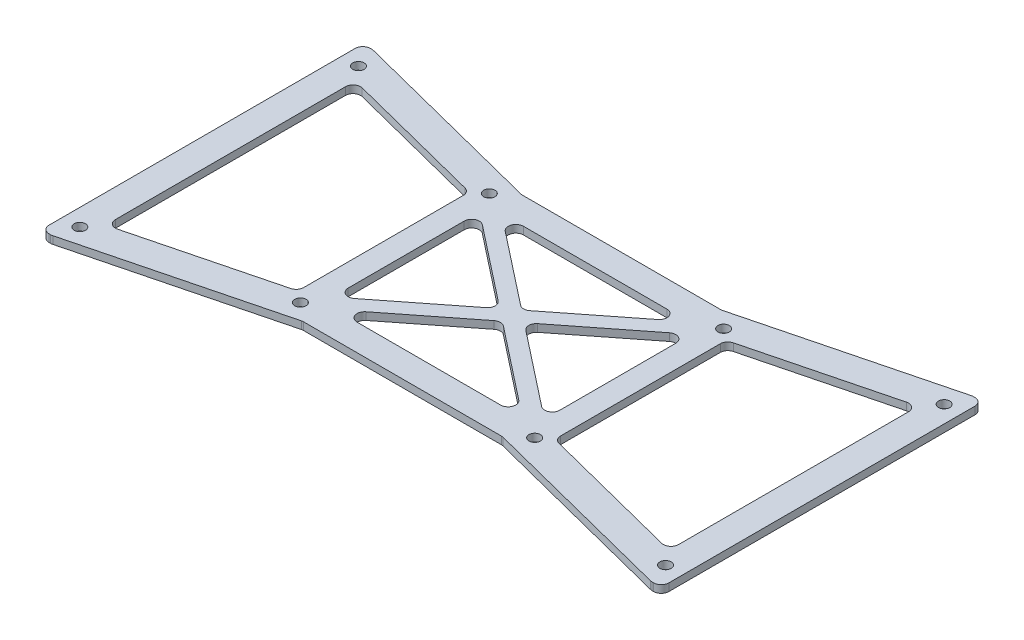
SolidWorks part; units mm, degrees
material "Thornel Mat VMA"
ref_plane "前视基准面" through (0, 0, 0) normal (0, 0, 1) x (1, 0, 0)
ref_plane "上视基准面" through (0, 0, 0) normal (0, 1, 0) x (1, 0, 0)
ref_plane "右视基准面" through (0, 0, 0) normal (1, 0, 0) x (0, 0, -1)
sketch "草图1" plane through (0, 0, 0) normal (0, 1, 0) x (1, 0, 0)
  line L1 (-82, -42.5) -> (82, -42.5)
  line L2 (-82, -42.5) -> (-82, 42.5)
  line L3 (-82, 42.5) -> (82, 42.5)
  line L4 (82, -42.5) -> (82, 42.5)
  line L5 (0, 42.5) -> (0, -42.5) construction
  line L6 (-82, 0) -> (82, 0) construction
  point P0 (0, 0)
  dimension "D1" = 164
  dimension "D2" = 85
extrude "凸台-拉伸1" add sketch "草图1" along normal blind 2
sketch "草图2" plane through (0, 2, 0) normal (0, 1, 0) x (1, 0, 0)
  line L1 (-31, -25) -> (31, -25) construction
  line L2 (-31, -25) -> (-31, 25) construction
  line L3 (-31, 25) -> (31, 25) construction
  line L4 (31, -25) -> (31, 25) construction
  line L5 (0, 25) -> (0, -25) construction
  line L6 (-31, 0) -> (31, 0) construction
  circle A0 centre (31, 25) radius 1.5
  circle A1 centre (-31, 25) radius 1.5
  circle A2 centre (-31, -25) radius 1.5
  circle A3 centre (31, -25) radius 1.5
  point P0 (0, 0)
  dimension "D3" = 3
  dimension "D1" = 62
  dimension "D2" = 50
extrude "切除-拉伸1" cut sketch "草图2" against normal blind 2
sketch "草图4" plane through (0, 2, 0) normal (0, 1, 0) x (1, 0, 0)
  line L1 (-28, -22) -> (28, -22)
  line L2 (-28, -22) -> (-28, 22)
  line L3 (-28, 22) -> (28, 22)
  line L4 (28, -22) -> (28, 22)
  line L5 (0, 22) -> (0, -22) construction
  line L6 (-28, 0) -> (28, 0) construction
  circle A0 centre (-31, 25) radius 1.5 construction
  point P0 (0, 0)
  dimension "D1" = 3
  dimension "D2" = 3
extrude "切除-拉伸3" cut sketch "草图4" against normal blind 10
sketch "草图7" plane through (0, 2, 0) normal (0, 1, 0) x (1, 0, 0)
  line L0 (-28, 22) -> (28, -22) construction
  line L1 (-28, -22) -> (28, 22) construction
  line L2 (-29.2356, 20.4274) -> (26.7644, -23.5726)
  line L3 (-26.7644, -23.5726) -> (29.2356, 20.4274)
  line L4 (-26.7644, 23.5726) -> (29.2356, -20.4274)
  line L5 (-29.2356, -20.4274) -> (26.7644, 23.5726)
  arc A0 (-29.2356, 20.4274) -> (-26.7644, 23.5726) centre (-28, 22) cw
  arc A1 (26.7644, -23.5726) -> (29.2356, -20.4274) centre (28, -22) ccw
  arc A2 (-26.7644, -23.5726) -> (-29.2356, -20.4274) centre (-28, -22) cw
  arc A3 (29.2356, 20.4274) -> (26.7644, 23.5726) centre (28, 22) ccw
  line M13 (-28, 22) -> (28, 22)
  line M14 (28, 22) -> (28, -22)
  line M15 (28, -22) -> (-28, -22)
  line M16 (-28, -22) -> (-28, 22)
  dimension "D1" = 2
  dimension "D2" = 2
extrude "凸台-拉伸2" add sketch "草图7" against normal up to surface (2 mm away) contours L5 L3 L2 M16 M15 | L5 L2 L3 L4 | L5 L4 L3 M14 M13 | L4 L3 L2 M15 M14 | L2 L5 L4 M13 M16 up to face at (0, 0, 0)
sketch "草图9" plane through (0, 2, 0) normal (0, 1, 0) x (1, 0, 0)
  circle A0 centre (77.5, -36.8695) radius 1.5 construction
  circle A1 centre (77.5, 36.8695) radius 1.5 construction
  circle A2 centre (77.5, -36.8695) radius 1.5
  circle A3 centre (77.5, 36.8695) radius 1.5
extrude "切除-拉伸6" cut sketch "草图9" against normal blind 10
mirror "镜向3" about plane through (0, 0, 0) normal (1, 0, 0) of "切除-拉伸6"
sketch "草图11" plane through (0, 0, 0) normal (0, -1, 0) x (1, 0, 0)
  line L0 (-77.5, 36.8695) -> (-31, 25) construction
  line L1 (-31, 25) -> (-31, -25) construction
  line L2 (-31, -25) -> (-77.5, -36.8695) construction
  line L3 (-77.5, -36.8695) -> (-77.5, 36.8695) construction
  line L4 (-74.5, 33.0076) -> (-34, 22.6696)
  line L5 (-34, 22.6696) -> (-34, -22.6696)
  line L6 (-34, -22.6696) -> (-74.5, -33.0076)
  line L7 (-74.5, -33.0076) -> (-74.5, 33.0076)
  dimension "D1" = 3
extrude "切除-拉伸7" cut sketch "草图11" against normal blind 10
mirror "镜向4" about plane through (0, 0, 0) normal (1, 0, 0) of "切除-拉伸7"
sketch "草图12" plane through (0, 0, 0) normal (0, -1, 0) x (1, 0, 0)
  line L0 (-77.5, 36.8695) -> (-31, 25) construction
  line L1 (-79.3418, 42.5) -> (-26.4543, 29)
  line L2 (-82, 42.5) -> (82, 42.5) construction
  line L3 (-26.4543, 29) -> (26.4543, 29)
  line L4 (26.4543, 29) -> (79.3418, 42.5)
  line L5 (79.3418, 42.5) -> (-79.3418, 42.5)
  line L6 (24.7628, 22) -> (-24.7628, 22) construction
  line L7 (0, -0.6763) -> (0, 42.5) construction
  dimension "D1" = 5
  dimension "D2" = 7
extrude "切除-拉伸8" cut sketch "草图12" against normal blind 10
mirror "镜向5" about plane through (0, 0, 0) normal (0, 0, 1) of "切除-拉伸8"
fillet "圆角3" radius 2 20 edges at (0, 1, -2.5435) (24.7628, 1, -22) (-24.7628, 1, -22) (-3.2372, 1, 0) (-28, 1, -19.4565) (-28, 1, 19.4565) (0, 1, 2.5435) (-24.7628, 1, 22) (24.7628, 1, 22) (3.2372, 1, 0) (28, 1, 19.4565) (28, 1, -19.4565) (-34, 1, 22.6696) (-74.5, 1, 33.0076) (74.5, 1, -33.0076) (34, 1, -22.6696) (34, 1, 22.6696) (74.5, 1, 33.0076) (-34, 1, -22.6696) (-74.5, 1, -33.0076)
fillet "圆角4" radius 2 12 edges at (-26.4543, 1, -29) (26.4543, 1, -29) (79.3418, 1, -42.5) (82, 1, -42.5) (82, 1, 42.5) (79.3418, 1, 42.5) (26.4543, 1, 29) (-26.4543, 1, 29) (-79.3418, 1, 42.5) (-82, 1, 42.5) (-82, 1, -42.5) (-79.3418, 1, -42.5)
equation "\"D2@草图4\"=\"D1@草图4\""
